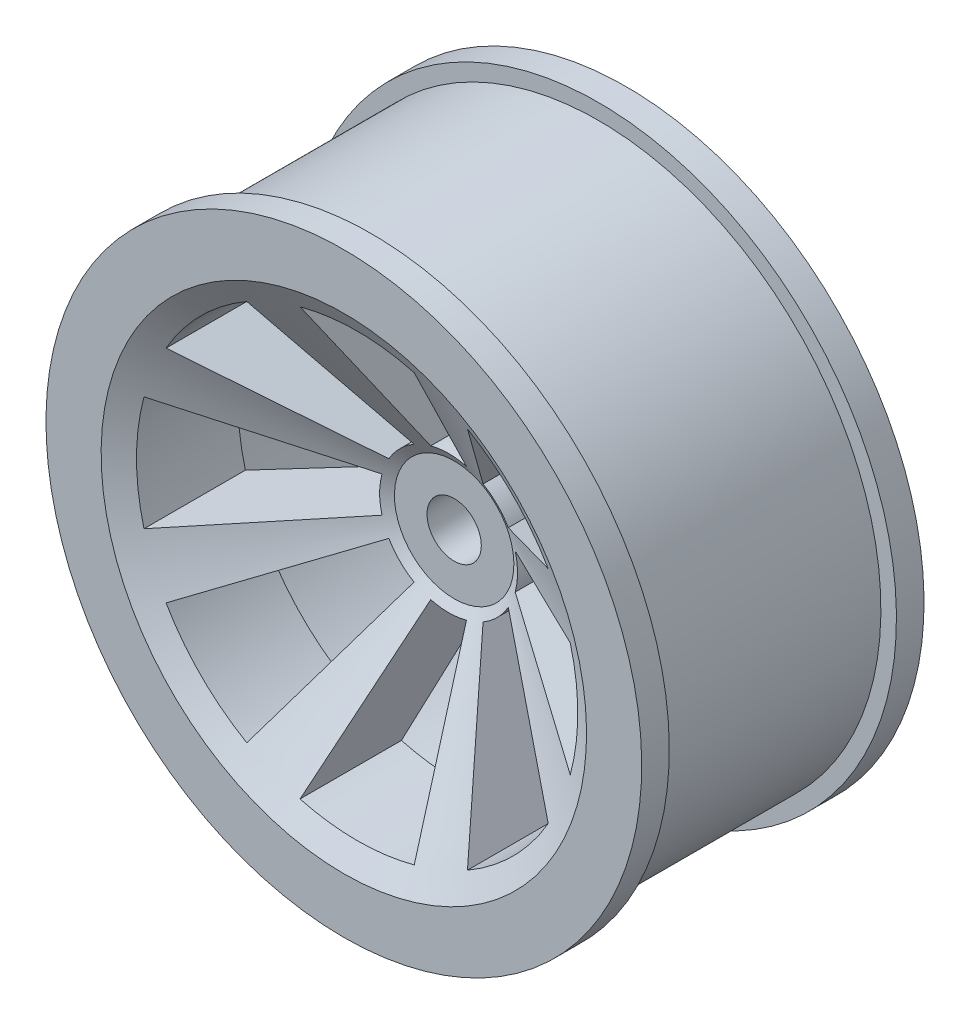
SolidWorks part; units mm, degrees
ref_plane "Front Plane" through (0, 0, 0) normal (0, 0, 1) x (1, 0, 0)
ref_plane "Top Plane" through (0, 0, 0) normal (0, 1, 0) x (1, 0, 0)
ref_plane "Right Plane" through (0, 0, 0) normal (1, 0, 0) x (0, 0, -1)
sketch "Sketch1" plane through (0, 0, 0) normal (1, 0, 0) x (0, 0, -1)
  line L0 (-6.61, 0) -> (1.61, 0)
  line L3 (1.61, 2.6) -> (1.61, 5.5)
  line L4 (1.61, 5.5) -> (-7.28, 22.352)
  line L5 (-7.28, 22.352) -> (9.23, 22.352)
  line L6 (9.23, 22.352) -> (9.23, 27.432)
  line L7 (9.23, 27.432) -> (6.69, 27.432)
  line L8 (6.69, 27.432) -> (6.69, 26)
  line L9 (6.69, 26) -> (-14.23, 26)
  line L10 (-14.23, 26) -> (-14.23, 27.432)
  line L11 (-14.23, 27.432) -> (-16.77, 27.432)
  line L12 (-16.77, 27.432) -> (-16.77, 22.352)
  line L13 (-16.77, 22.352) -> (-6.61, 5.5)
  line L14 (-6.61, 5.5) -> (-6.61, 0)
  line L15 (1.61, 2.6) -> (1.61, 0)
  point P0 (0, 0)
  dimension "D1" = 26
  dimension "D2" = 27.432
  dimension "D3" = 26
  dimension "D4" = 2.54
  dimension "D5" = 9.49
  dimension "D6" = 8.22
  dimension "D7" = 6.61
  dimension "D9" = 5.08
  dimension "D10" = 10.16
  dimension "D11" = 5.5
revolve "Revolve1" add sketch "Sketch1" angle 360 about L0
sketch "Sketch2" plane through (0, 0, 16.77) normal (0, 0, 1) x (1, 0, 0)
  line L0 (-5.2592, 19.6276) -> (-1.6435, 6.1336)
  line L1 (1.6435, 6.1336) -> (5.2592, 19.6276)
  arc A0 (-5.2592, 19.6276) -> (5.2592, 19.6276) centre (0, 0) cw
  arc A1 (-1.6435, 6.1336) -> (1.6435, 6.1336) centre (0, 0) cw
  point P4 (0, 20.32)
  point P7 (0, 6.35)
  dimension "D1" = 20.32
  dimension "D3" = 6.35
  dimension "D2" = 30
extrude "Cut-Extrude1" cut sketch "Sketch2" against normal up to surface (10.5619 mm away)
pattern_circular "CirPattern1" count 8 over 360 about axis through (0, 0, 0) along (0, 0, 1) of "Cut-Extrude1"
chamfer "Chamfer1" distance 2.54 angle 45 1 edges at (0, -22.352, -9.23)
sketch "Sketch3" plane through (0, 0, 6.61) normal (0, 0, 1) x (1, 0, 0)
  circle A0 centre (0, 0) radius 2.5
  dimension "D1" = 5
extrude "Cut-Extrude2" cut sketch "Sketch3" against normal up to next
